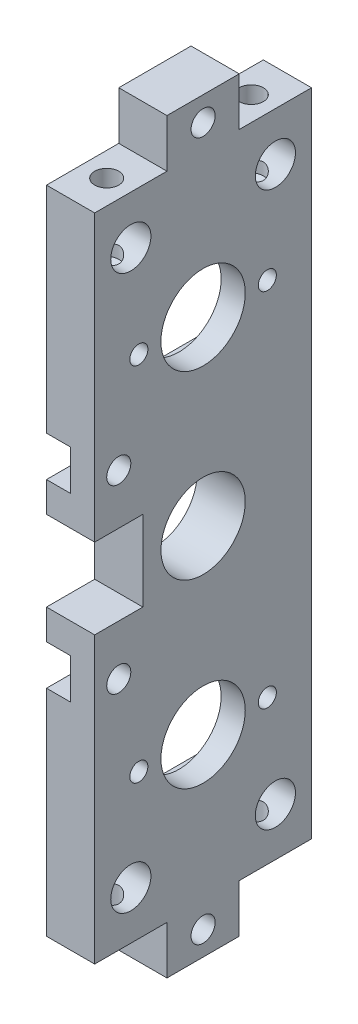
SolidWorks part; units mm, degrees
material "HDPE-green"
ref_plane "Front Plane" through (0, 0, 0) normal (0, 0, 1) x (1, 0, 0)
ref_plane "Top Plane" through (0, 0, 0) normal (0, 1, 0) x (1, 0, 0)
ref_plane "Right Plane" through (0, 0, 0) normal (1, 0, 0) x (0, 0, -1)
sketch "Sketch2" plane through (0, 0, 0) normal (1, 0, 0) x (0, 0, -1)
  line L1 (27, -81) -> (-27, -81)
  line L2 (27, -81) -> (27, 81)
  line L3 (27, 81) -> (-27, 81)
  line L4 (-27, -81) -> (-27, 81)
  line L5 (27, -81) -> (-27, 81) construction
  line L6 (27, 81) -> (-27, -81) construction
  circle A0 centre (0, 0) radius 10.5
  circle A1 centre (0, 45) radius 10.5
  circle A2 centre (0, -45) radius 10.5
  point P0 (0, 0)
  dimension "D3" = 21
  dimension "D4" = 21
  dimension "D5" = 21
  dimension "D6" = 45
  dimension "D7" = 45
  dimension "D1" = 162
  dimension "D2" = 54
extrude "Boss-Extrude1" add sketch "Sketch2" along normal blind 12
sketch "Sketch3" plane through (12, 0, 0) normal (1, 0, 0) x (0, 0, -1)
  line L0 (-27, -81) -> (27, -81) construction
  line L1 (-9, -81) -> (9, -81)
  line L2 (-9, -81) -> (-9, -93)
  line L3 (-9, -93) -> (9, -93)
  line L4 (9, -81) -> (9, -93)
  circle A0 centre (0, -45) radius 10.5 construction
  dimension "D1" = 12
  dimension "D2" = 18
  dimension "D3" = 9
extrude "Boss-Extrude2" add sketch "Sketch3" against normal blind 12
mirror "Mirror1" about plane through (0, 0, 0) normal (0, 1, 0) of "Boss-Extrude2"
sketch "Sketch4" plane through (12, 0, 0) normal (1, 0, 0) x (0, 0, -1)
  line L0 (-22.8937, -45) -> (24.0018, -45) construction
  line L1 (-19.0059, 0) -> (18.3719, 0) construction
  line L2 (-24.3784, 45) -> (28.6327, 45) construction
  circle A0 centre (-16, -45) radius 2.25
  circle A1 centre (16, -45) radius 2.25
  circle A2 centre (0, -45) radius 10.5 construction
  dimension "D1" = 4.5
  dimension "D2" = 4.5
  dimension "D3" = 16
  dimension "D4" = 16
extrude "Cut-Extrude1" cut sketch "Sketch4" against normal up to next
pattern_linear "LPattern1" count 2 spacing 90 along (0, 1, 0) of "Cut-Extrude1"
sketch "Sketch5" plane through (0, 0, 0) normal (-1, 0, 0) x (0, 0, 1)
  line L0 (-16.9926, 60.5) -> (16.9926, 60.5)
  line L1 (16.9926, 29.5) -> (-16.9926, 29.5)
  line L2 (-16.9926, -29.5) -> (16.9926, -29.5)
  line L3 (16.9926, -60.5) -> (-16.9926, -60.5)
  line L8 (-16.9926, 15.5) -> (16.9926, 15.5) [skipped]
  line L9 (16.9926, -15.5) -> (-16.9926, -15.5) [skipped]
  line L10 (-16.9926, 15.5) -> (16.9926, 15.5) [skipped]
  line L11 (16.9926, -15.5) -> (-16.9926, -15.5) [skipped]
  arc A0 (-16.9926, 60.5) -> (-16.9926, 29.5) centre (0, 45) ccw
  arc A1 (16.9926, 29.5) -> (16.9926, 60.5) centre (0, 45) ccw
  arc A2 (-16.9926, -29.5) -> (-16.9926, -60.5) centre (0, -45) ccw
  arc A3 (16.9926, -60.5) -> (16.9926, -29.5) centre (0, -45) ccw
  arc A8 (16.9926, -15.5) -> (16.9926, 15.5) centre (0, 0) ccw [skipped]
  arc A9 (-16.9926, 15.5) -> (-16.9926, -15.5) centre (0, 0) ccw [skipped]
  arc A10 (-16.9926, 15.5) -> (-16.9926, -15.5) centre (0, 0) ccw [skipped]
  arc A11 (16.9926, -15.5) -> (16.9926, 15.5) centre (0, 0) ccw [skipped]
  dimension "D1" = 2
  dimension "D2" = 2
extrude "Cut-Extrude2" cut sketch "Sketch5" against normal blind 6
sketch "Sketch6" plane through (0, 0, 0) normal (-1, 0, 0) x (0, 0, 1)
  line L0 (27, 81) -> (27, -81) construction
  line L1 (39, -10) -> (15, -10)
  line L2 (39, -10) -> (39, 10)
  line L3 (39, 10) -> (15, 10)
  line L4 (15, -10) -> (15, 10)
  line L5 (39, -10) -> (15, 10) construction
  line L6 (39, 10) -> (15, -10) construction
  point P0 (27, 0)
  dimension "D1" = 20
  dimension "D2" = 24
extrude "Cut-Extrude3" cut sketch "Sketch6" against normal up to next
sketch "Sketch7" plane through (0, 0, 0) normal (-1, 0, 0) x (0, 0, 1)
  line L0 (21, 19.0778) -> (21, -26.4331) construction
  line L1 (15, 10) -> (15, -10) construction
  circle A0 centre (21, 22.5) radius 3
  circle A1 centre (21, -22.5) radius 3
  point P6 (15, 0)
  dimension "D1" = 6
  dimension "D2" = 6
  dimension "D3" = 45
  dimension "D4" = 22.5
extrude "Cut-Extrude4" cut sketch "Sketch7" against normal up to next
sketch "Sketch8" plane through (0, 0, 0) normal (-1, 0, 0) x (0, 0, 1)
  line L0 (21, 27.5) -> (27, 27.5)
  line L1 (27, 81) -> (27, 10) construction
  line L2 (27, 27.5) -> (27, 17.5)
  line L3 (27, 17.5) -> (21, 17.5)
  line L4 (21, -27.5) -> (27, -27.5)
  line L5 (27, -10) -> (27, -81) construction
  line L6 (27, -27.5) -> (27, -17.5)
  line L7 (27, -17.5) -> (21, -17.5)
  arc A0 (21, 27.5) -> (21, 17.5) centre (21, 22.5) ccw
  arc A1 (21, -17.5) -> (21, -27.5) centre (21, -22.5) ccw
  dimension "D1" = 10
  dimension "D2" = 10
extrude "Cut-Extrude5" cut sketch "Sketch8" against normal blind 6
sketch "Sketch9" plane through (0, 0, 0) normal (-1, 0, 0) x (0, 0, 1)
  line L0 (-40.0762, -69) -> (40.2298, -69) construction
  line L1 (9, -93) -> (-9, -93) construction
  line L2 (-27, -81) -> (-27, 81) construction
  line L3 (27, -27.5) -> (27, -81) construction
  circle A0 centre (-18, -69) radius 5
  circle A1 centre (18, -69) radius 5
  dimension "D2" = 10
  dimension "D3" = 10
  dimension "D4" = 9
  dimension "D5" = 9
  dimension "D1" = 24
extrude "Cut-Extrude6" cut sketch "Sketch9" against normal up to next
hole_wizard "Hole1" positions "Sketch11" profile "Sketch10" legacy end condition up to next
sketch "Sketch11" plane through (0, 0, 0) normal (-1, 0, 0) x (0, 0, 1)
  line L0 (9, -81) -> (9, -93) construction
  line L1 (9, -93) -> (-9, -93) construction
  point P0 (0, -87)
  dimension "D1" = 9
  dimension "D2" = 6
sketch "Sketch10" plane through (0, -87, 0) normal (0, 1, 0) x (0, 0, 1)
  line L0 (0, 0) -> (0, 12.001)
  line L1 (0, 12.001) -> (3, 12.001)
  line L2 (3, 12.001) -> (3, 6)
  line L3 (3, 6) -> (5, 6)
  line L4 (5, 6) -> (5, 0)
  line L5 (5, 0) -> (0, 0)
  line L6 (0, 110) -> (0, -10) construction
  dimension "Diameter" = 6
  dimension "Depth" = 12.001
  dimension "C-Bore Diameter" = 10
  dimension "C-Bore Depth" = 6
hole_wizard "Ø6.0 (6) Diameter Hole1" positions "Sketch14" profile "Sketch13" hole size "Ø6.0" standard "ISO"
sketch "Sketch14" plane through (0, -81, 0) normal (0, -1, 0) x (1, 0, 0)
  line L0 (0, -9) -> (0, -27) construction
  line L1 (0, 27) -> (0, 9) construction
  line L2 (12, 27) -> (0, 27) construction
  line L3 (12, -27) -> (0, -27) construction
  point P0 (6, -18)
  point P1 (6, 18)
  dimension "D1" = 6
  dimension "D2" = 6
  dimension "D3" = 9
  dimension "D4" = 9
sketch "Sketch13" plane through (6, -81, -18) normal (1, 0, 0) x (0, 0, -1)
  line L0 (0, 0) -> (0, 20.8026)
  line L1 (0, 20.8026) -> (3, 19)
  line L2 (3, 19) -> (3, 0)
  line L5 (3, 0) -> (0, 0)
  line L10 (0, 20.8026) -> (-3, 19) construction
  line L11 (0, -6.35) -> (0, 107.95) construction
  dimension "Hole Dia." = 6
  dimension "Hole Depth" = 19
  dimension "Drill Angle" = 118
mirror "Mirror2" about plane through (0, 0, 0) normal (0, 1, 0) of "Cut-Extrude6", "Hole1", "Ø6.0 (6) Diameter Hole1"
